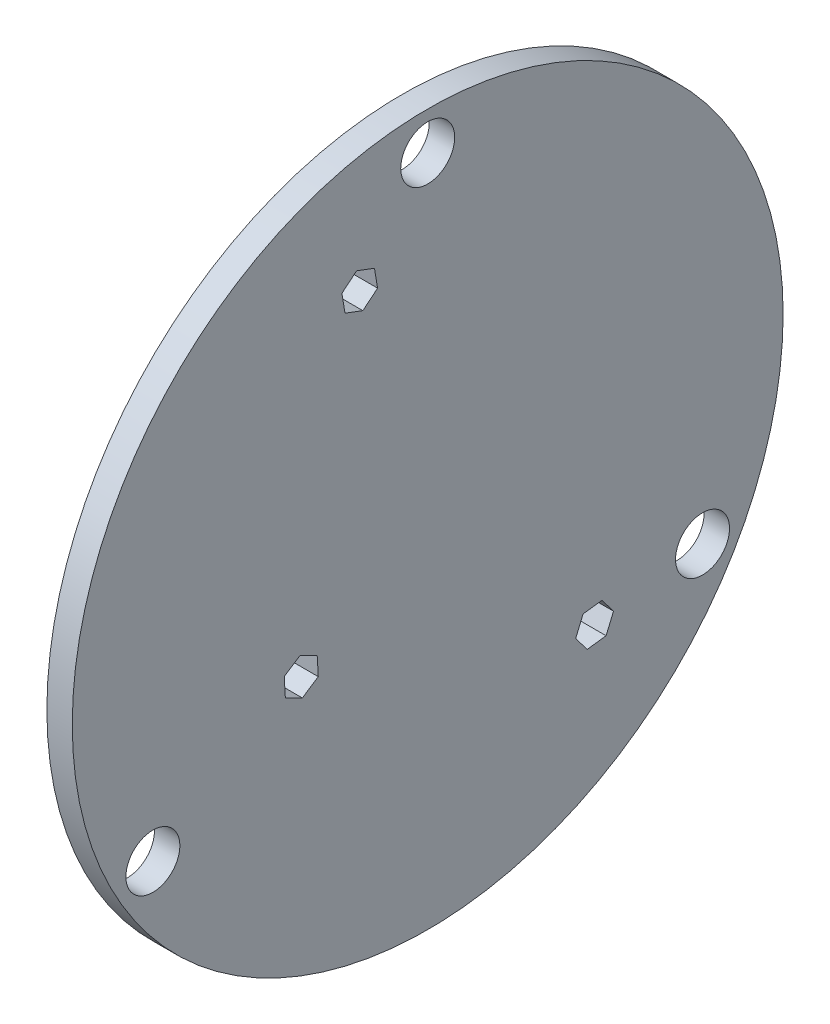
SolidWorks part; units mm, degrees
ref_plane "Ebene vorne" through (0, 0, 0) normal (0, 0, 1) x (1, 0, 0)
ref_plane "Ebene oben" through (0, 0, 0) normal (0, 1, 0) x (1, 0, 0)
ref_plane "Ebene rechts" through (0, 0, 0) normal (1, 0, 0) x (0, 0, -1)
sketch "Sketch1" plane through (0, 0, 0) normal (1, 0, 0) x (0, 0, -1)
  circle A0 centre (0, 0) radius 56
  dimension "D1" = 112
extrude "Boss-Extrude1" add sketch "Sketch1" along normal blind 4
sketch "Sketch2" plane through (0, 0, 0) normal (-1, 0, 0) x (0, 0, 1)
  circle A1 centre (0, 50) radius 4.25
  circle A2 centre (43.3013, -25) radius 4.25
  circle A3 centre (-43.3013, -25) radius 4.25
  point P9 (0, 0)
  point P13 (0, 0)
  dimension "D4" = 3
  dimension "D2" = 50
extrude "Cut-Extrude1" cut sketch "Sketch2" against normal through all
sketch "Sketch3" [suppressed] plane through (0, 0, 0) normal (-1, 0, 0) x (0, 0, 1)
  line L0 (-30, -47.2864) -> (-30, -36.2864)
  line L1 (0, 56) -> (0, -56) construction
  line L2 (30, -47.2864) -> (30, -36.2864)
  line L3 (-30, -36.2864) -> (30, -36.2864)
  circle A0 centre (0, 0) radius 56 construction
  arc A2 (-30, -47.2864) -> (30, -47.2864) centre (0, 0) ccw
  dimension "D1" = 11
  dimension "D2" = 60
extrude "Cut-Extrude2" [suppressed] cut sketch "Sketch3" against normal through all
sketch "Sketch4" plane through (4, 0, 0) normal (1, 0, 0) x (0, 0, -1)
  line L25 (27.4594, -24.776) -> (24.4806, -25.1504)
  line L26 (24.4806, -25.1504) -> (23.3154, -27.9173)
  line L27 (23.3154, -27.9173) -> (25.1291, -30.3098)
  line L28 (25.1291, -30.3098) -> (28.1078, -29.9355)
  line L29 (28.1078, -29.9355) -> (29.273, -27.1686)
  line L30 (29.273, -27.1686) -> (27.4594, -24.776)
  line L31 (-13.0239, 34.6351) -> (-10.2126, 33.5815)
  line L32 (-10.2126, 33.5815) -> (-7.8945, 35.4893)
  line L33 (-7.8945, 35.4893) -> (-8.3877, 38.4508)
  line L34 (-8.3877, 38.4508) -> (-11.199, 39.5044)
  line L35 (-11.199, 39.5044) -> (-13.517, 37.5965)
  line L36 (-13.517, 37.5965) -> (-13.0239, 34.6351)
  line L37 (-17.2366, -12.8491) -> (-17.4092, -9.8519)
  line L38 (-17.4092, -9.8519) -> (-20.0912, -8.5027)
  line L39 (-20.0912, -8.5027) -> (-22.6006, -10.1509)
  line L40 (-22.6006, -10.1509) -> (-22.428, -13.1481)
  line L41 (-22.428, -13.1481) -> (-19.746, -14.4973)
  line L42 (-19.746, -14.4973) -> (-17.2366, -12.8491)
  circle A0 centre (26.2942, -27.5429) radius 2.6 construction
  circle A2 centre (-10.7058, 36.5429) radius 2.6 construction
  circle A3 centre (-19.9186, -11.5) radius 2.6 construction
  dimension "D1" = 5.2
  dimension "D2" = 5.2
extrude "Cut-Extrude3" cut sketch "Sketch4" against normal through all
